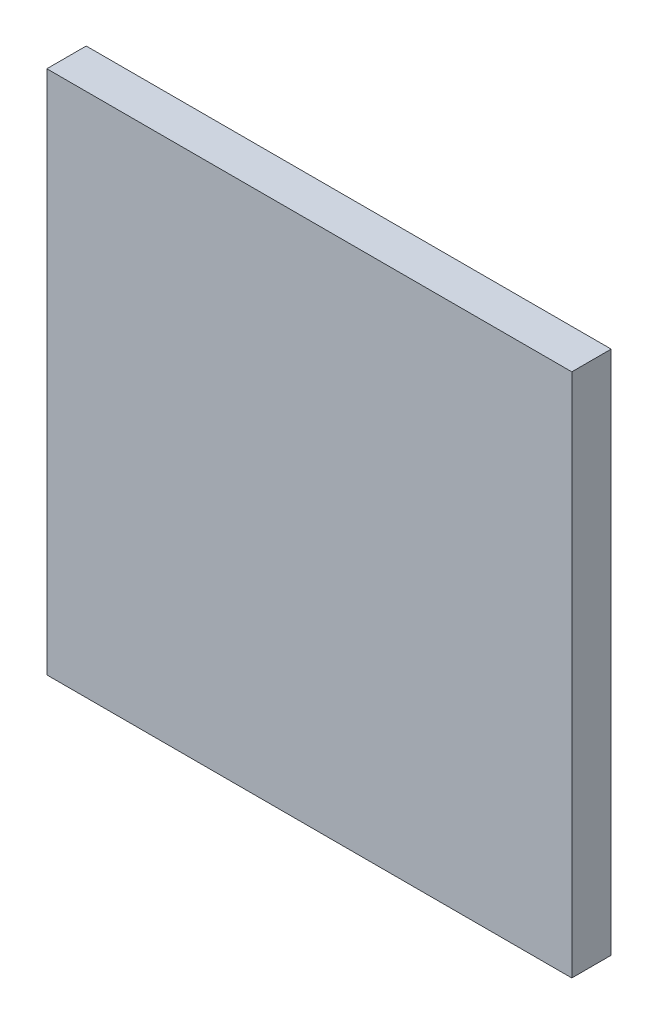
SolidWorks part; units mm, degrees
ref_plane "Front Plane" through (0, 0, 0) normal (0, 0, 1) x (1, 0, 0)
ref_plane "Top Plane" through (0, 0, 0) normal (0, 1, 0) x (1, 0, 0)
ref_plane "Right Plane" through (0, 0, 0) normal (1, 0, 0) x (0, 0, -1)
sketch "Sketch1" plane through (0, 0, 0) normal (0, 0, 1) x (1, 0, 0)
  line L0 (-7, 7) -> (7, 7)
  line L1 (7, 7) -> (7, -7)
  line L2 (7, -7) -> (-7, -7)
  line L3 (-7, -7) -> (-7, 7)
extrude "Component_Outline" add sketch "Sketch1" along normal blind 1.05 separate body
sketch3d "3DSketch1"
  line L0 (0, 0, 0) -> (1, 0, 0)
  line L1 (0, 0, 0) -> (0, 1, 0)
  line L2 (0, 0, 0) -> (0, 0, 1)
  point P0 (0, 0, 0)
